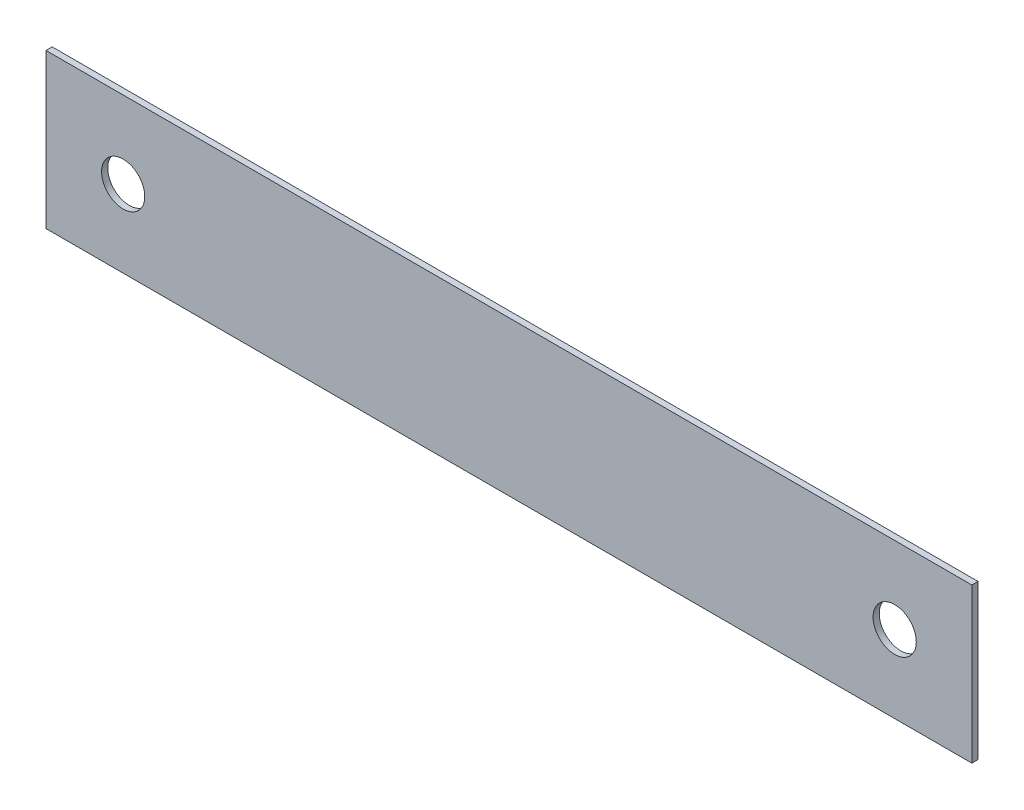
SolidWorks part; units mm, degrees
ref_plane "Alzado" through (0, 0, 0) normal (0, 0, 1) x (1, 0, 0)
ref_plane "Planta" through (0, 0, 0) normal (0, 1, 0) x (1, 0, 0)
ref_plane "Vista lateral" through (0, 0, 0) normal (1, 0, 0) x (0, 0, -1)
sketch "Croquis1" plane through (0, 0, 0) normal (0, 0, 1) x (1, 0, 0)
  line L0 (0, 0) -> (150, 0)
  line L1 (150, 0) -> (150, 25)
  line L2 (150, 25) -> (0, 25)
  line L3 (0, 25) -> (0, 0)
  circle A0 centre (12.5, 12.5) radius 3.5
  circle A1 centre (137.5, 12.5) radius 3.5
extrude "Saliente-Extruir1" add sketch "Croquis1" along normal blind 1
